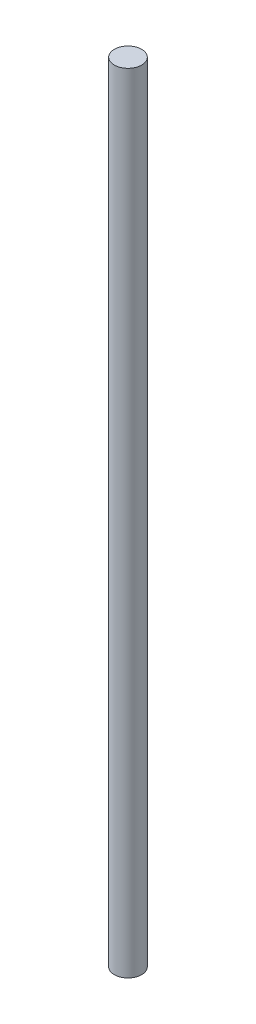
SolidWorks part; units mm, degrees
material "Plain Carbon Steel"
ref_plane "Front Plane" through (0, 0, 0) normal (0, 0, 1) x (1, 0, 0)
ref_plane "Top Plane" through (0, 0, 0) normal (0, 1, 0) x (1, 0, 0)
ref_plane "Right Plane" through (0, 0, 0) normal (1, 0, 0) x (0, 0, -1)
sketch "Sketch1" plane through (0, 0, 0) normal (0, 1, 0) x (1, 0, 0)
  circle A0 centre (0, 0) radius 15.875
  dimension "D1" = 31.75
extrude "Shaft extrusion" add sketch "Sketch1" along normal blind 914.4
